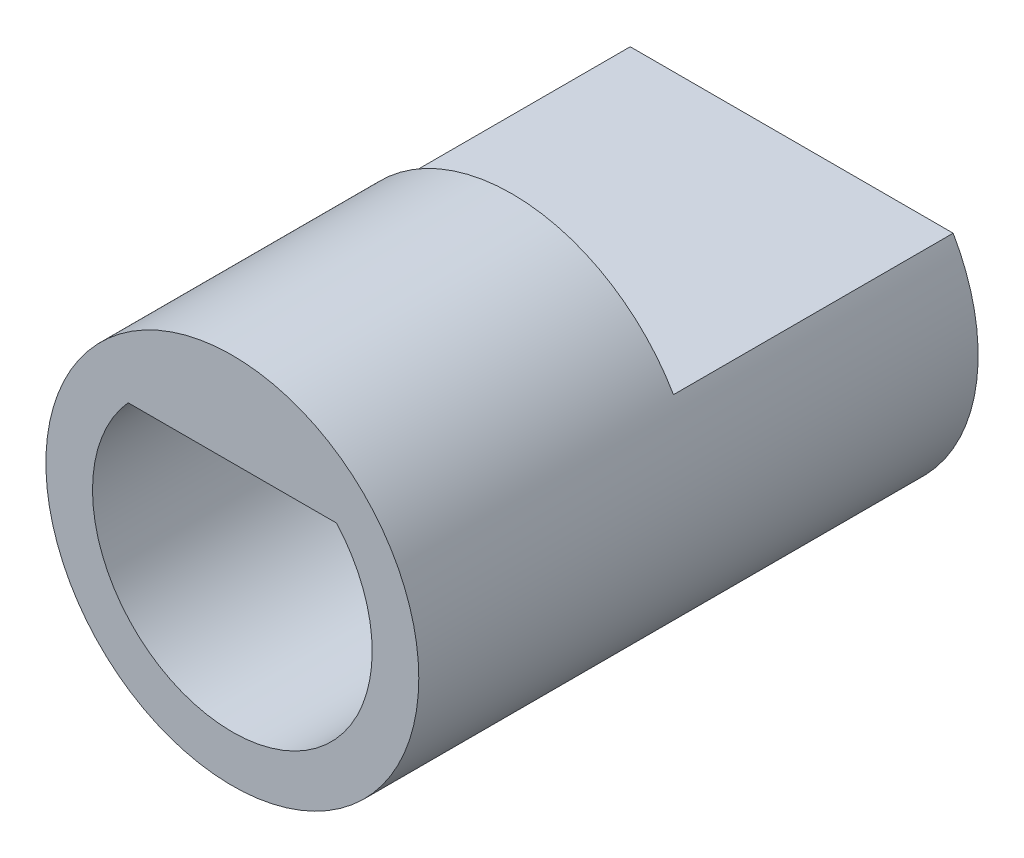
SolidWorks part; units mm, degrees
ref_plane "Спереди" through (0, 0, 0) normal (0, 0, 1) x (1, 0, 0)
ref_plane "Сверху" through (0, 0, 0) normal (0, 1, 0) x (1, 0, 0)
ref_plane "Справа" through (0, 0, 0) normal (1, 0, 0) x (0, 0, -1)
sketch "Sketch1" plane through (0, 0, 0) normal (0, 0, 1) x (1, 0, 0)
  circle A0 centre (0, 0) radius 2
extrude "Extrude1" add sketch "Sketch1" along normal blind 3
sketch "Sketch2" plane through (0, 0, 0) normal (0, 0, -1) x (-1, 0, 0)
  line L0 (0, -2) -> (0, 1)
  line L1 (0, 1) -> (-1.7321, 1)
  line L2 (0, 1) -> (1.7321, 1)
  arc A0 (-1.7321, 1) -> (1.7321, 1) centre (0, 0) ccw
extrude "Extrude2" add sketch "Sketch2" along normal blind 3 contours L1 A0 L0 | L0 A0 L2
sketch "Sketch3" plane through (0, 0, 3) normal (0, 0, 1) x (1, 0, 0)
  line L0 (0, -1.5) -> (0, 1)
  line L1 (0, 1) -> (2.0607, 1)
  line L2 (2.0607, 1) -> (-2.0436, 1)
  circle A0 centre (0, 0) radius 1.5
extrude "Extrude3" cut sketch "Sketch3" against normal blind 2.5 contours L2 A0 L0 | L0 A0 L1
